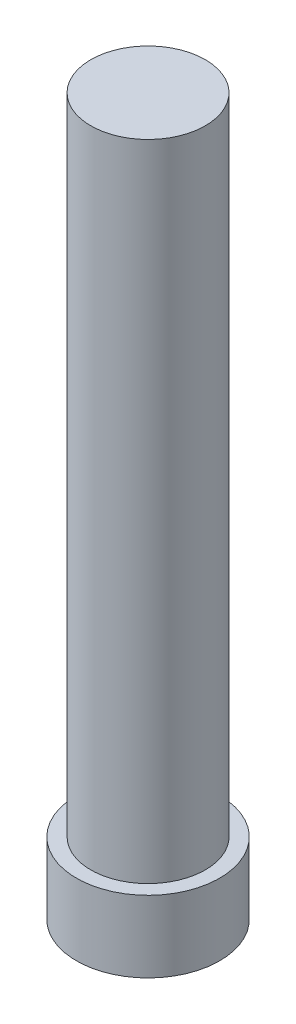
SolidWorks part; units mm, degrees
ref_plane "前视基准面" through (0, 0, 0) normal (0, 0, 1) x (1, 0, 0)
ref_plane "上视基准面" through (0, 0, 0) normal (0, 1, 0) x (1, 0, 0)
ref_plane "右视基准面" through (0, 0, 0) normal (1, 0, 0) x (0, 0, -1)
sketch "草图1" plane through (0, 0, 0) normal (0, 1, 0) x (1, 0, 0)
  circle A0 centre (0, 0) radius 4
extrude "凸台-拉伸1" add sketch "草图1" along normal blind 45
sketch "草图2" plane through (0, 0, 0) normal (0, -1, 0) x (1, 0, 0)
  circle A0 centre (0, 0) radius 5
extrude "凸台-拉伸2" add sketch "草图2" along normal blind 5
